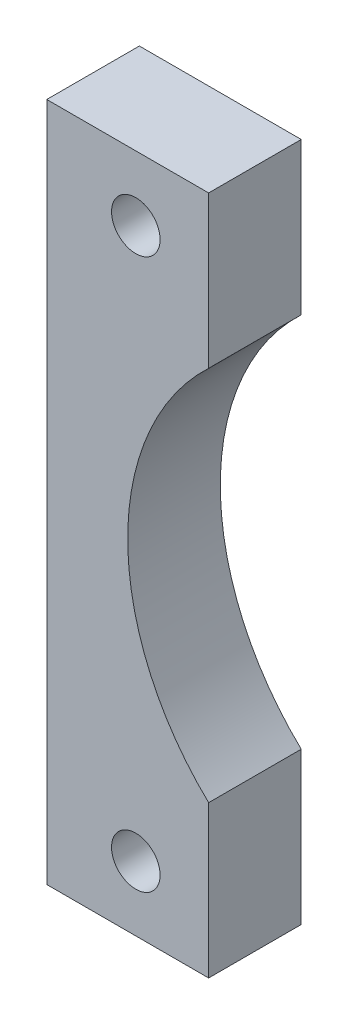
SolidWorks part; units mm, degrees
ref_plane "Front Plane" through (0, 0, 0) normal (0, 0, 1) x (1, 0, 0)
ref_plane "Top Plane" through (0, 0, 0) normal (0, 1, 0) x (1, 0, 0)
ref_plane "Right Plane" through (0, 0, 0) normal (1, 0, 0) x (0, 0, -1)
sketch "Sketch1" plane through (0, 0, 0) normal (0, 0, 1) x (1, 0, 0)
  line L0 (0, 0) -> (10, 0)
  line L1 (0, 0) -> (0, -42)
  line L2 (0, -42) -> (10, -42)
  line L3 (10, -42) -> (10, -32.619)
  line L4 (10, 0) -> (10, -9.381)
  arc A0 (10, -9.381) -> (10, -32.619) centre (21, -21) ccw
  circle A1 centre (5.5, -38) radius 1.5
  circle A2 centre (5.5, -4) radius 1.5
  dimension "D3" = 32
  dimension "D4" = 21
  dimension "D5" = 21
  dimension "D6" = 4.5
  dimension "D7" = 4.5
  dimension "D8" = 4
  dimension "D9" = 3
  dimension "D10" = 4
  dimension "D11" = 3
  dimension "D1" = 10
  dimension "D2" = 42
extrude "Boss-Extrude1" add sketch "Sketch1" along normal blind 5.72
